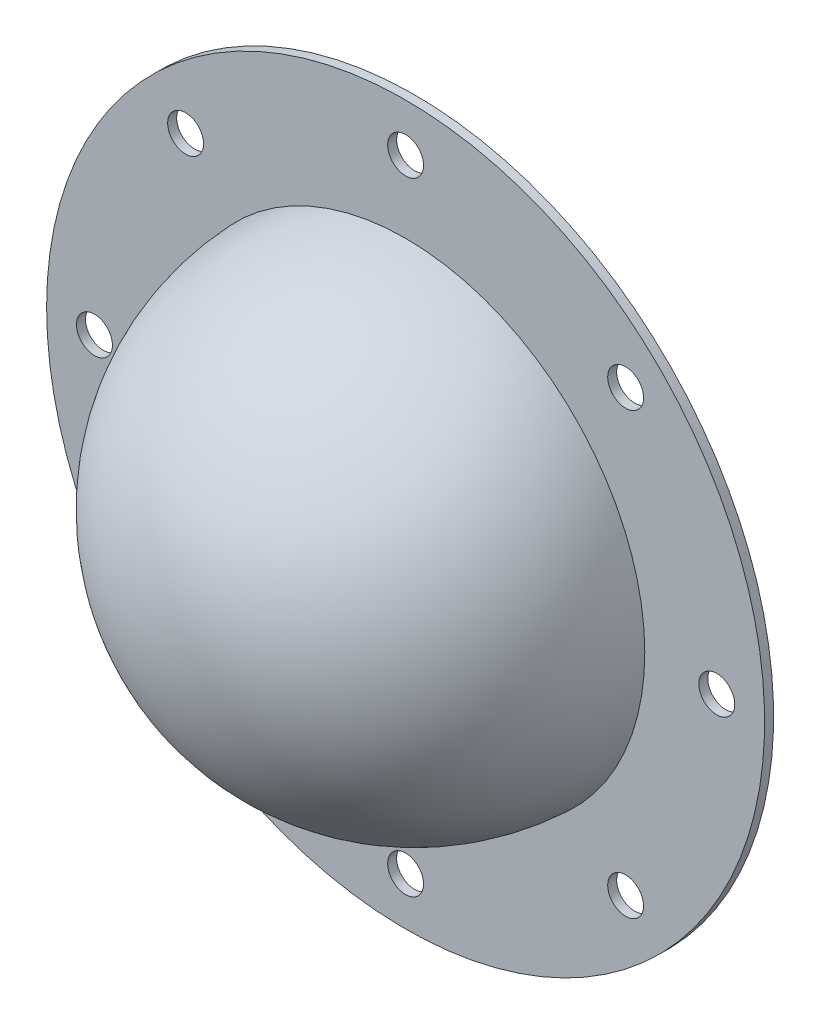
SolidWorks part; units mm, degrees
ref_plane "前视基准面" through (0, 0, 0) normal (0, 0, 1) x (1, 0, 0)
ref_plane "上视基准面" through (0, 0, 0) normal (0, 1, 0) x (1, 0, 0)
ref_plane "右视基准面" through (0, 0, 0) normal (1, 0, 0) x (0, 0, -1)
sketch "草图1" plane through (0, 0, 0) normal (1, 0, 0) x (0, 0, -1)
  line L0 (-40, 0) -> (40, 0)
  arc A0 (40, 0) -> (-40, 0) centre (0, 0) ccw
  dimension "D1" = 80
revolve "旋转1" add sketch "草图1" angle 360 about L0
sketch "草图2" plane through (0, 0, 0) normal (0, 0, 1) x (1, 0, 0)
  circle A0 centre (-18.7622, 13.2377) radius 101.541
extrude "切除-拉伸1" cut sketch "草图2" against normal blind 92
sketch "草图3" plane through (0, 0, 0) normal (0, 1, 0) x (1, 0, 0)
  line L0 (40, 0) -> (-40, 0) construction
  line L1 (0, 38.5) -> (0, -38.5)
  arc A0 (0, -38.5) -> (0, 38.5) centre (0, 0) ccw
  arc A1 (-40, 0) -> (40, 0) centre (0, 0) ccw construction
  dimension "D1" = 1.5
revolve "切除-旋转1" cut sketch "草图3" angle 360 about L1
sketch "草图4" plane through (0, 0, 0) normal (0, 0, -1) x (-1, 0, 0)
  circle A0 centre (0, 0) radius 39
  circle A1 centre (0, 0) radius 60
  dimension "D1" = 120
  dimension "D2" = 78
extrude "凸台-拉伸1" add sketch "草图4" against normal blind 1.5
sketch "草图5" plane through (0, 0, 0) normal (0, 1, 0) x (1, 0, 0)
  line L0 (-45, 0) -> (-45, 2)
  line L1 (-45, 2) -> (-43, 2)
  line L2 (-43, 2) -> (-43, 0)
  line L3 (60, 0) -> (-60, 0) construction
  line L4 (-43, 0) -> (-45, 0)
  line L5 (-60, 0) -> (-60, -1.5) construction
  line L6 (0, 24.6607) -> (0, -55.0563) construction
  dimension "D1" = 2
  dimension "D2" = 2
  dimension "D3" = 15
revolve "旋转2" add sketch "草图5" angle 360 about L6
sketch "草图6" plane through (0, 0, 1.5) normal (0, 0, 1) x (1, 0, 0)
  line L0 (0, 103.6862) -> (0, -89.0554) construction
  line L1 (-108.4804, 0) -> (90.8339, 0) construction
  circle A0 centre (52, 0) radius 3
  dimension "D1" = 6
  dimension "D2" = 52
extrude "切除-拉伸2" cut sketch "草图6" against normal blind 20
pattern_circular "阵列(圆周)1" count 8 over 360 about axis through (0, 0, 0) along (0, 0, 1) of "切除-拉伸2"
